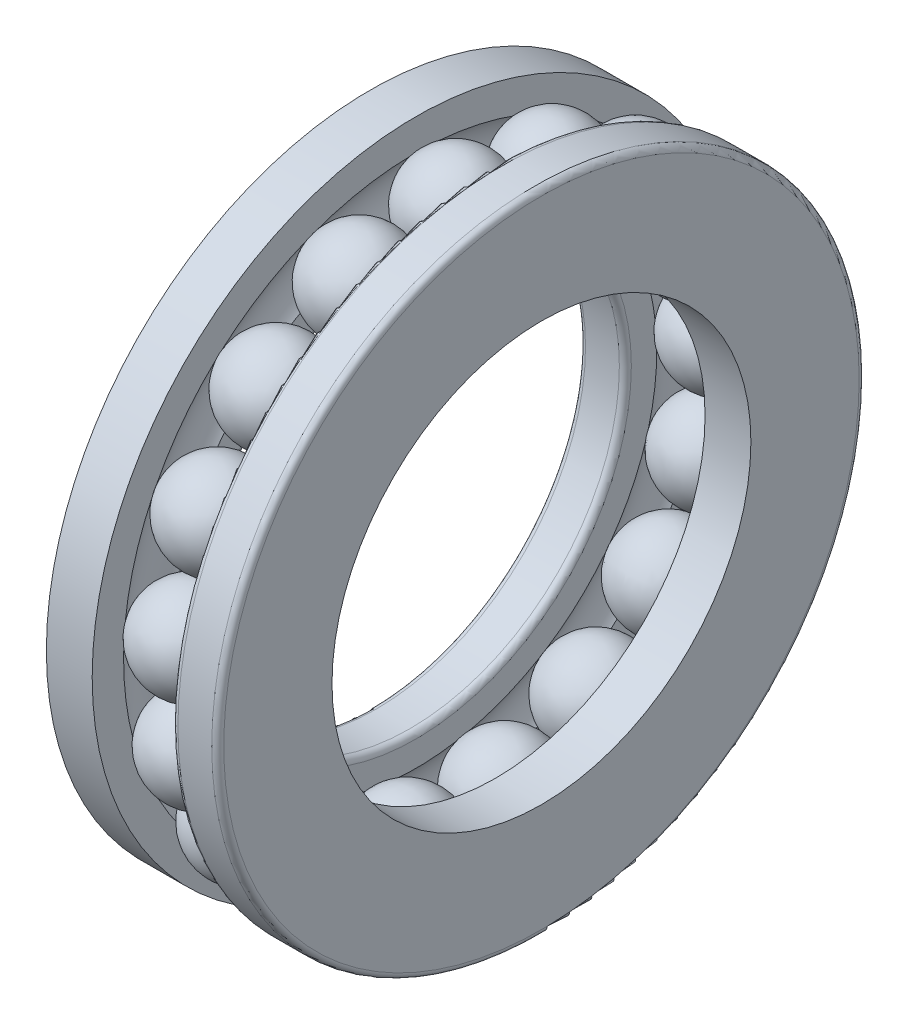
SolidWorks part; units mm, degrees
ref_plane "Plane1" through (0, 0, 0) normal (0, 0, 1) x (1, 0, 0)
ref_plane "Plane2" through (0, 0, 0) normal (0, 1, 0) x (1, 0, 0)
ref_plane "Plane3" through (0, 0, 0) normal (1, 0, 0) x (0, 0, -1)
sketch "Clipboard" plane through (0, 0, 0) normal (0, 0, 1) x (1, 0, 0)
  line L0 (-10, 0) -> (10, 0) construction
  line L1 (0, 0) -> (21.3836, -6.5376)
  line L2 (0, 0) -> (27.3662, 35.0271)
  line L3 (0, 0) -> (13.7666, -17.6205)
  line L4 (0, 0) -> (-22.3471, -0.7804)
  dimension "BallCLRad" = 44.45
  dimension "Count" = 52
  dimension "Show_count" = 52
  dimension "Max_count" = 17
  dimension "Min_count" = 2
sketch "InnRacSke" plane through (0, 0, 0) normal (0, 0, 1) x (1, 0, 0)
  line L0 (-6.6469, 40.1573) -> (-6.6469, 34.925)
  line L1 (-6.6469, 34.925) -> (-14.2875, 34.925)
  line L2 (-14.2875, 34.925) -> (-14.2875, 53.975)
  line L3 (-14.2875, 53.975) -> (-6.6469, 53.975)
  line L4 (-6.6469, 53.975) -> (-6.6469, 48.7427)
  line L5 (-34.925, 0) -> (34.925, 0) construction
  line L6 (0, 0) -> (0, 25.4) construction
  arc A2 (-6.6469, 48.7427) -> (-6.6469, 40.1573) centre (0, 44.45) ccw
  dimension "BallCLRad" = 44.45
  dimension "Ball_diameter" = 15.825
  dimension "ID" = 69.85
  dimension "OD" = 107.95
  dimension "Width" = 28.575
  dimension "gap" = 13.2937
revolve "Race" add sketch "InnRacSke" angle 360 about L5
ref_axis "Axis1" through (-50, 0, 0) along (1, 0, 0)
sketch "BalDetSke" plane through (0, 0, 0) normal (0, 0, 1) x (1, 0, 0)
  line L0 (-7.9375, 44.45) -> (7.9375, 44.45)
  line L1 (-14.5732, 44.45) -> (14.5732, 44.45) construction
  arc A0 (7.9375, 44.45) -> (-7.9375, 44.45) centre (0, 44.45) cw
  dimension "BallCLRad" = 44.45
  dimension "Ball_diameter" = 15.875
revolve "BallDetailed" add sketch "BalDetSke" angle 360 about L1
sketch "BalSimSke" plane through (0, 0, 0) normal (0, 0, 1) x (1, 0, 0)
  line L0 (-25.4, 0) -> (25.4, 0) construction
  circle A0 centre (0, 44.45) radius 7.9375
  dimension "BallCLRad" = 44.45
  dimension "Ball_diameter" = 15.875
revolve "BallsSimplified" [suppressed] add sketch "BalSimSke" angle 360 about L0
mirror "Mirror1" about plane through (0, 0, 0) normal (1, 0, 0) of "Race"
fillet "Fillet" radius 1 4 edges at (6.6469, 0, -53.975) (14.2875, 0, -53.975) (-6.6469, 0, -34.925) (-14.2875, 0, -34.925)
pattern_circular "BallsDetailed" count 17 every 21.176 about axis through (-50, 0, 0) along (1, 0, 0) of "BallDetailed"
sketch "CagSpiSke" plane through (0, 0, 0) normal (0, 0, 1) x (1, 0, 0)
  line L0 (1.9844, 35.7188) -> (1.9844, 53.1812)
  line L1 (1.9844, 53.1812) -> (-1.9844, 53.1812)
  line L2 (-1.9844, 53.1812) -> (-1.9844, 35.7188)
  line L3 (-1.9844, 35.7188) -> (1.9844, 35.7188)
  line L4 (-34.925, 0) -> (34.925, 0) construction
  line L5 (0, 0) -> (0, 50.8) construction
  dimension "Thickness" = 3.9688
  dimension "ID" = 71.4375
  dimension "OD" = 106.3625
revolve "CageSpine" [suppressed] add sketch "CagSpiSke" angle 360 about L4
equation "\"BallCLRad@Clipboard\" =  ( \"OD@InnRacSke\" + \"ID@InnRacSke\" )  / 4"
equation "\"BallCLRad@BalSimSke\" = \"BallCLRad@Clipboard\""
equation "\"BallCLRad@BalDetSke\" = \"BallCLRad@Clipboard\""
equation "\"BallCLRad@InnRacSke\" = \"BallCLRad@Clipboard\""
equation "\"Ball_diameter@InnRacSke\" = \"Ball_diameter@BalDetSke\" - 0.05"
equation "\"Ball_diameter@BalSimSke\" = \"Ball_diameter@BalDetSke\""
equation "\"Max_count@Clipboard\" = int( 3.14159265 / atn(( \"Ball_diameter@BalDetSke\" / 2) / sqr( \"BallCLRad@Clipboard\"  *  \"BallCLRad@Clipboard\" - ( \"Ball_diameter@BalDetSke\" / 2) *  ( \"Ball_diameter@BalDetSke\" / 2))))"
equation "\"Max_count@Clipboard\" = ((sgn( \"Max_count@Clipboard\" - \"Count@Clipboard\" )-1)*( \"Max_count@Clipboard\" - \"Count@Clipboard\" ))/-2+ \"Count@Clipboard\""
equation "\"Count@BallsDetailed\" = int( \"Show_count@Clipboard\" ) "
equation "\"Count@BallsDetailed\" = ((sgn( \"Count@BallsDetailed\" - \"Max_count@Clipboard\" )-1)*( \"Count@BallsDetailed\" - \"Max_count@Clipboard\" ))/-2+ \"Max_count@Clipboard\""
equation "\"Count@BallsDetailed\" = ((sgn( \"Count@BallsDetailed\" - \"Min_count@Clipboard\" )+1)*( \"Count@BallsDetailed\" - \"Min_count@Clipboard\"))/2 +\"Min_count@Clipboard\""
equation "\"Angle@BallsDetailed\" = 360.0 / \"Max_count@Clipboard\""
equation "\"Angle@CageSpine\" =  \"Angle@BallsDetailed\" * ( \"Count@BallsDetailed\" -1 + int( \"Count@BallsDetailed\" / \"Max_count@Clipboard\" ) )  + 0.001 -  int( \"Count@BallsDetailed\" / \"Max_count@Clipboard\" ) * 0.001"
equation "\"Angle@CageSpine\" =  \"Angle@CageSpine\" * int( \"Min_count@Clipboard\" / 2) + int(1 / \"Min_count@Clipboard\")  * 0.001"
equation "\"Thickness@CagSpiSke\" =  \"Ball_diameter@BalDetSke\" * 0.25"
equation "\"OD@CagSpiSke\" = ( \"OD@InnRacSke\" + ( \"BallCLRad@Clipboard\" * 2 + \"Ball_diameter@BalDetSke\" )) / 2"
equation "\"ID@CagSpiSke\" = ( \"ID@InnRacSke\" + ( \"BallCLRad@Clipboard\" * 2 - \"Ball_diameter@BalDetSke\" )) / 2"
